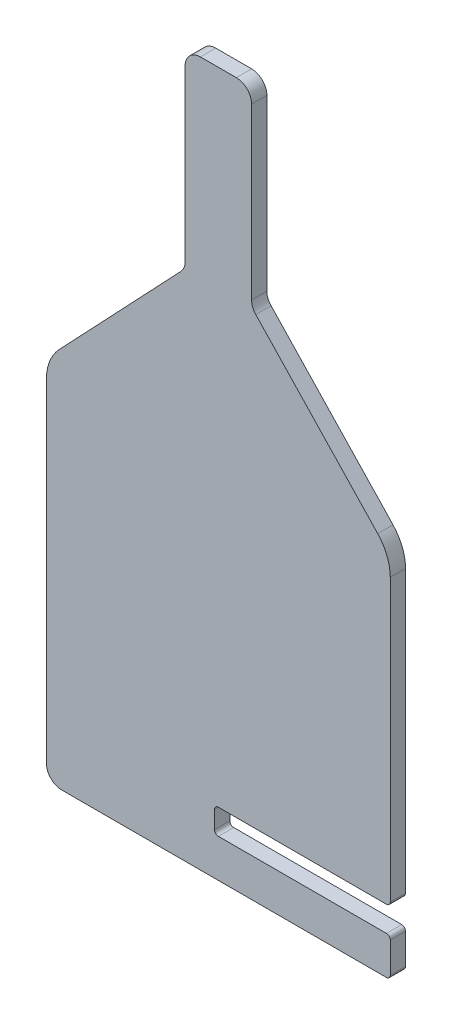
SolidWorks part; units mm, degrees
ref_plane "Alzado" through (0, 0, 0) normal (0, 0, 1) x (1, 0, 0)
ref_plane "Planta" through (0, 0, 0) normal (0, 1, 0) x (1, 0, 0)
ref_plane "Vista lateral" through (0, 0, 0) normal (1, 0, 0) x (0, 0, -1)
sketch "Croquis1" plane through (0, 0, 0) normal (0, 0, 1) x (1, 0, 0)
  line L0 (-4.35, 20) -> (-22.5, 0.8287)
  line L1 (-4.35, 45) -> (4.35, 45)
  line L2 (-22.5, 0.8287) -> (-22.5, -47.1713)
  line L3 (-22.5, -47.1713) -> (22.5, -47.1713)
  line L4 (22.5, 0.8287) -> (22.5, -47.1713)
  line L5 (-4.35, 45) -> (4.35, 45)
  line L6 (-4.35, 45) -> (-4.35, 20)
  line L8 (4.35, 45) -> (4.35, 19.999)
  line L9 (4.35, 19.999) -> (22.5, 0.8287)
  line L10 (0, 72.8664) -> (0, -82.626) construction
  dimension "D1" = 45
  dimension "D2" = 25
  dimension "D3" = 4.35
  dimension "D4" = 22.5
  dimension "D5" = 45
  dimension "D6" = 4.35
  dimension "D7" = 26.3993
  dimension "D8" = 26.4
  dimension "D9" = 48
  dimension "D10" = 48
extrude "Saliente-Extruir1" add sketch "Croquis1" along normal blind 2 contours L6 L0 L2 L3 L4 L9 L8 L1
sketch "Croquis3" plane through (0, 0, 2) normal (0, 0, 1) x (1, 0, 0)
  line L0 (22.5, 0.8287) -> (22.5, -47.1713) construction
  line L1 (22.5, -38.8713) -> (-0.5, -38.8713)
  line L2 (22.5, -38.8713) -> (22.5, -42.1713)
  line L3 (22.5, -42.1713) -> (-0.5, -42.1713)
  line L4 (-0.5, -38.8713) -> (-0.5, -42.1713)
  line L5 (-22.5, -47.1713) -> (22.5, -47.1713) construction
  dimension "D1" = 3.3
  dimension "D2" = 5
  dimension "D3" = 23
extrude "Cortar-Extruir2" cut sketch "Croquis3" against normal up to surface (2 mm away) up to face at (0, 4.6642, 0)
fillet "Redondeo1" radius 2 5 edges at (-22.5, -47.1713, 1) (-4.35, 20, 1) (-4.35, 45, 1) (4.35, 19.999, 1) (4.35, 45, 1)
fillet "Redondeo2" radius 6 2 edges at (-22.5, 0.8287, 1) (22.5, 0.8287, 1)
fillet "Redondeo3" radius 0.5 5 edges at (-0.5, -42.1713, 1) (-0.5, -38.8713, 1) (22.5, -42.1713, 1) (22.5, -38.8713, 1) (22.5, -47.1713, 1)
